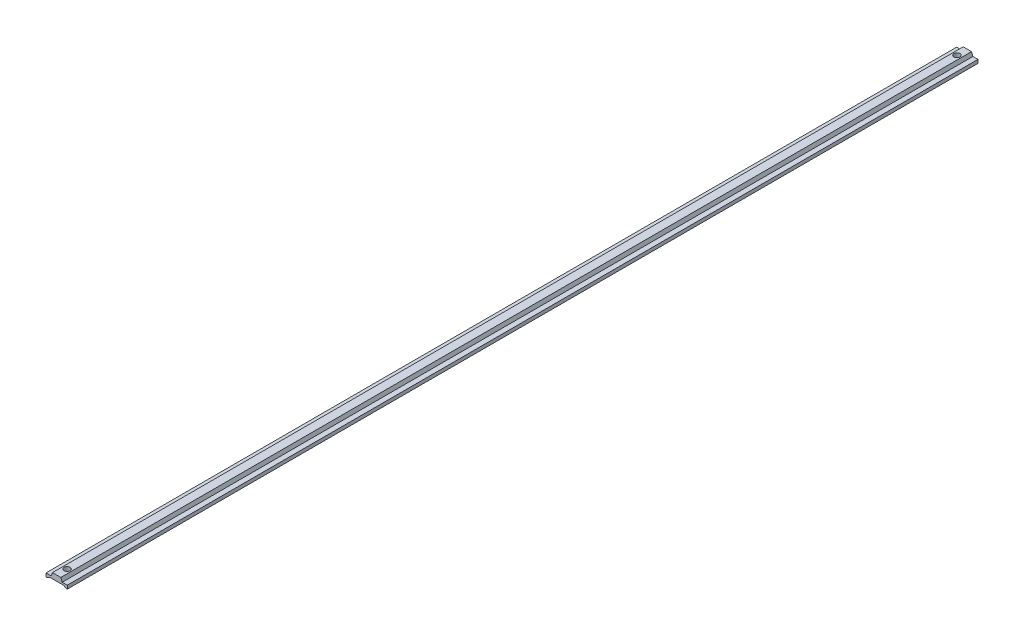
SolidWorks part; units mm, degrees
material "ﾅｲﾛﾝ 101"
ref_plane "正面" through (0, 0, 0) normal (0, 0, 1) x (1, 0, 0)
ref_plane "平面" through (0, 0, 0) normal (0, 1, 0) x (1, 0, 0)
ref_plane "右側面" through (0, 0, 0) normal (1, 0, 0) x (0, 0, -1)
sketch "ｽｹｯﾁ1" plane through (0, 0, 0) normal (0, 0, 1) x (1, 0, 0)
  line L0 (3, 0) -> (-3, 0)
  line L1 (-3, 0) -> (-4, -2.5)
  line L2 (-4, -2.5) -> (-7.65, -2.5)
  line L3 (-7.65, -2.5) -> (-7.65, -5)
  line L4 (-7.65, -5) -> (-6.65, -5)
  line L5 (-6.65, -5) -> (-5.05, -3.9)
  line L6 (-5.05, -3.9) -> (5.05, -3.9)
  line L7 (0, -3.9) -> (0, 0)
  line L8 (6.65, -5) -> (5.05, -3.9)
  line L9 (7.65, -5) -> (6.65, -5)
  line L10 (7.65, -2.5) -> (7.65, -5)
  line L11 (4, -2.5) -> (7.65, -2.5)
  line L12 (3, 0) -> (4, -2.5)
  dimension "D1" = 3
  dimension "D2" = 1
  dimension "D3" = 5
  dimension "D4" = 2.5
  dimension "D5" = 5.05
  dimension "D6" = 1.1
  dimension "D7" = 7.65
  dimension "D8" = 1
extrude "ﾎﾞｽ - 押し出し1" add sketch "ｽｹｯﾁ1" along normal blind 655 contours L12 L0 L7 L6 L8 L9 L10 L11 | L6 L7 L0 L1 L2 L3 L4 L5
sketch "ｽｹｯﾁ2" plane through (0, 0, 0) normal (0, 1, 0) x (1, 0, 0)
  line L0 (0, 0) -> (0, -655) construction
  line L1 (3, -655) -> (-3, -655) construction
  line L2 (3, -327.5) -> (0, -327.5) construction
  line L3 (3, -655) -> (3, 0) construction
  circle A0 centre (0, -7.5) radius 2.15
  circle A1 centre (0, -647.5) radius 2.15
  dimension "D1" = 4.3
  dimension "D2" = 7.5
extrude "ｶｯﾄ - 押し出し1" cut sketch "ｽｹｯﾁ2" against normal up to surface (3.9 mm away) up to face at (0, -3.9, 327.5)
